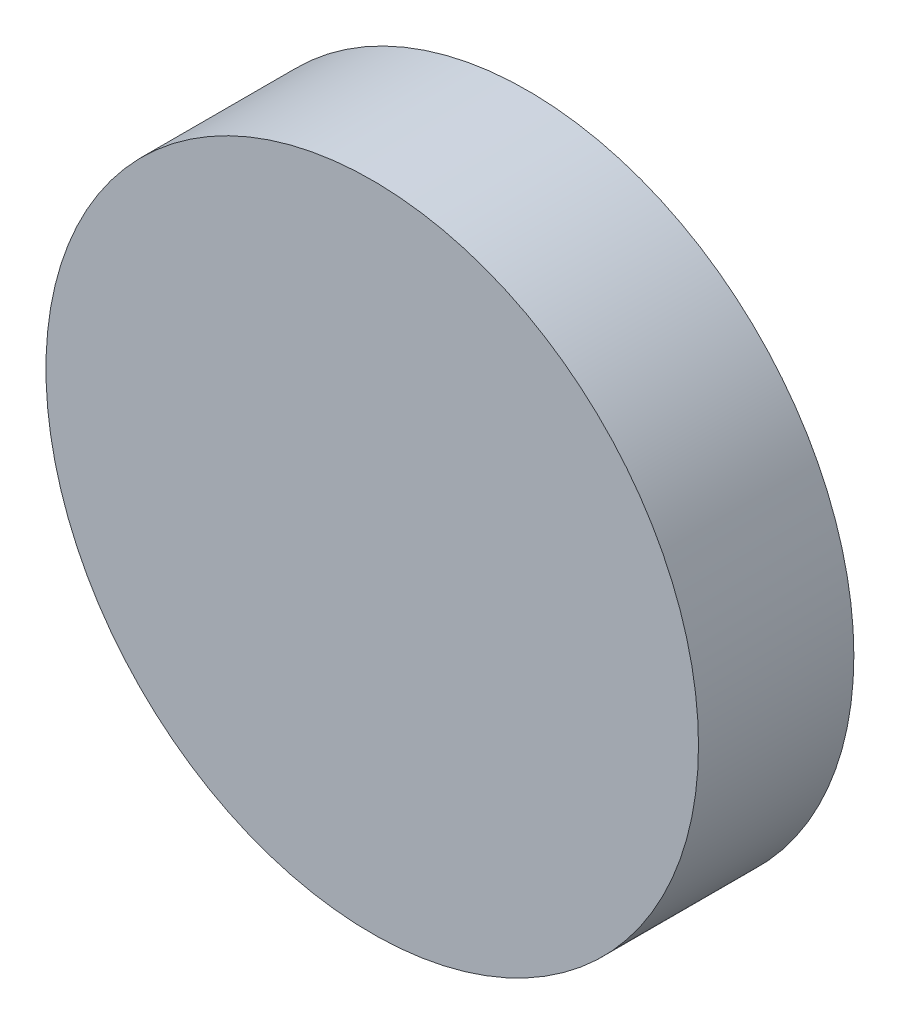
SolidWorks part; units mm, degrees
ref_plane "Front Plane" through (0, 0, 0) normal (0, 0, 1) x (1, 0, 0)
ref_plane "Top Plane" through (0, 0, 0) normal (0, 1, 0) x (1, 0, 0)
ref_plane "Right Plane" through (0, 0, 0) normal (1, 0, 0) x (0, 0, -1)
sketch "Sketch1" plane through (0, 0, 0) normal (0, 0, 1) x (1, 0, 0)
  circle A0 centre (0, 0) radius 21
  dimension "D1" = 42
extrude "Boss-Extrude1" add sketch "Sketch1" along normal blind 10
